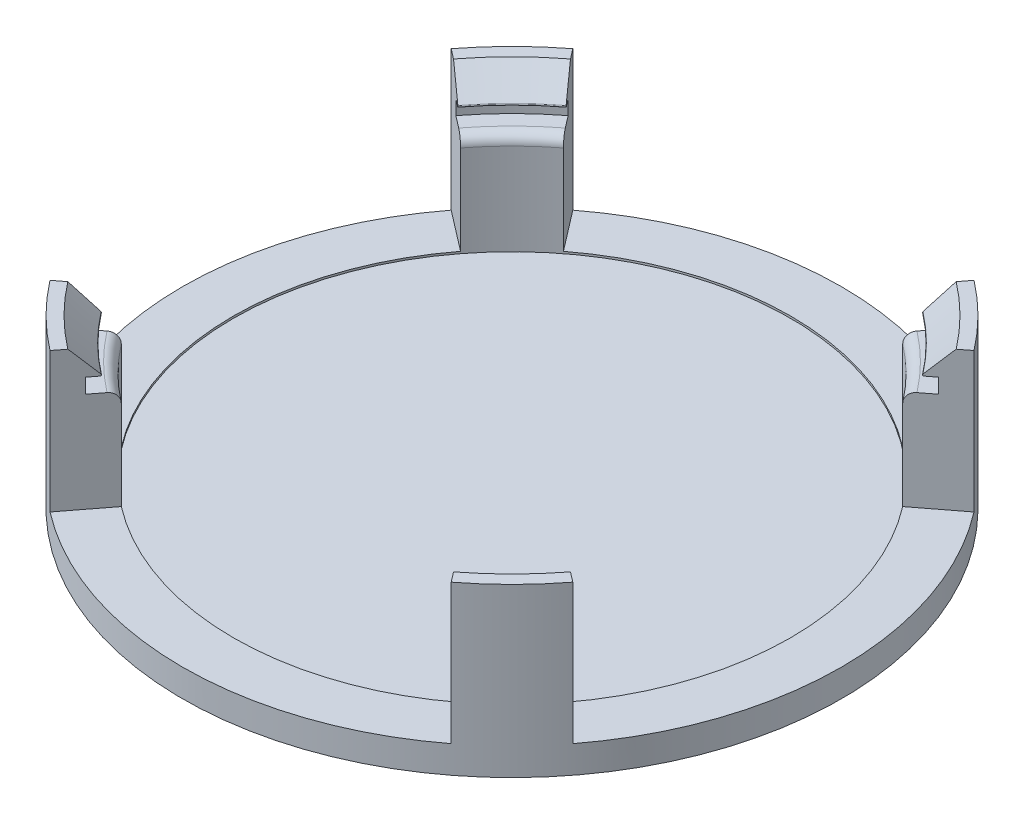
SolidWorks part; units mm, degrees
ref_plane "Front Plane" through (0, 0, 0) normal (0, 0, 1) x (1, 0, 0)
ref_plane "Top Plane" through (0, 0, 0) normal (0, 1, 0) x (1, 0, 0)
ref_plane "Right Plane" through (0, 0, 0) normal (1, 0, 0) x (0, 0, -1)
sketch "Sketch1" plane through (0, 0, 0) normal (0, 0, 1) x (1, 0, 0)
  line L0 (0, 0) -> (-41.148, 0)
  line L1 (-41.148, 0) -> (-41.148, 20.8915)
  line L2 (-41.148, 20.8915) -> (-39.5605, 20.8915)
  line L3 (-39.5605, 20.8915) -> (-36.3855, 17.7165)
  line L4 (-36.3855, 17.7165) -> (-37.973, 17.7165)
  line L5 (-37.973, 17.7165) -> (-37.973, 15.875)
  line L6 (-37.973, 15.875) -> (-34.798, 15.875)
  line L7 (-34.798, 15.875) -> (-34.798, 3.175)
  line L8 (-34.798, 3.175) -> (0, 3.175)
  line L9 (0, 3.175) -> (0, 0)
  dimension "D1" = 37.973
  dimension "D2" = 3.175
  dimension "D3" = 3.175
  dimension "D4" = 12.7
  dimension "D5" = 1.8415
  dimension "D6" = 1.5875
  dimension "D7" = 3.175
  dimension "D8" = 3.175
  dimension "D9" = 1.5875
revolve "Revolve1" add sketch "Sketch1" angle 360 about L9
sketch "Sketch2" plane through (0, 20.8915, 0) normal (0, 1, 0) x (1, 0, 0)
  line L0 (0, 0) -> (-25.0493, 32.6449)
  line L1 (0, 0) -> (-32.6449, 25.0493)
  line L2 (0, 41.148) -> (0, -41.148) construction
  line L3 (0, 0) -> (32.6449, 25.0493)
  line L4 (0, 0) -> (29.096, 29.096) construction
  line L5 (0, 0) -> (25.0493, 32.6449)
  line L6 (0, 0) -> (25.0493, -32.6449)
  line L7 (0, 0) -> (29.096, -29.096) construction
  line L8 (0, 0) -> (-29.096, 29.096) construction
  line L9 (0, 0) -> (32.6449, -25.0493)
  line L10 (0, 0) -> (-32.6449, -25.0493)
  line L11 (0, 0) -> (-29.096, -29.096) construction
  line L12 (0, 0) -> (-25.0493, -32.6449)
  arc A0 (-32.6449, 25.0493) -> (-32.6449, -25.0493) centre (0, 0) ccw
  arc A1 (25.0493, 32.6449) -> (-25.0493, 32.6449) centre (0, 0) ccw
  arc A2 (32.6449, -25.0493) -> (32.6449, 25.0493) centre (0, 0) ccw
  arc A3 (-25.0493, -32.6449) -> (25.0493, -32.6449) centre (0, 0) ccw
  point P20 (0, 0)
  circle M1 centre (0, 0) radius 41.148
  circle M2 centre (0, 0) radius 39.5605
  dimension "D1" = 15
  dimension "D2" = 45
  dimension "D3" = 4
  dimension "D5" = 7.5
extrude "Cut-Extrude3" cut sketch "Sketch2" against normal blind 17.4625 contours L0 L5 M2 | L5 L0 M2 M1 | L3 L9 M2 | L9 L3 M2 M1 | L6 L12 M2 | L12 L6 M2 M1 | L1 A0 L10
fillet "Fillet1" radius 0.127 4 edges at (-25.7284, 17.7165, 25.7284) (25.7284, 17.7165, 25.7284) (25.7284, 17.7165, -25.7284) (-25.7284, 17.7165, -25.7284)
fillet "Fillet2" radius 1.27 4 edges at (-24.6059, 15.875, -24.6059) (-24.6059, 15.875, 24.6059) (24.6059, 15.875, 24.6059) (24.6059, 15.875, -24.6059)
equation "\"0.0`\"=0.1"
